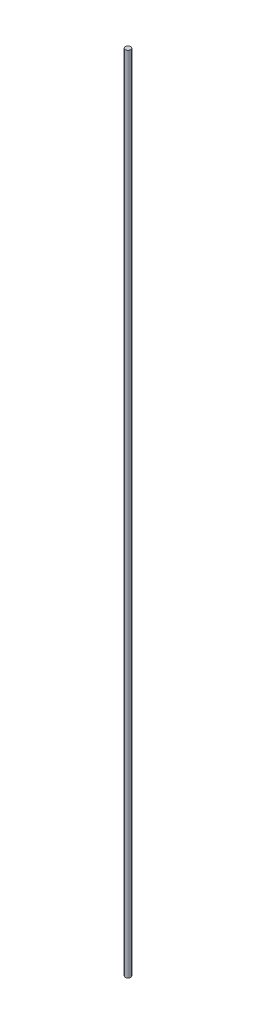
SolidWorks part; units mm, degrees
ref_plane "Front Plane" through (0, 0, 0) normal (0, 0, 1) x (1, 0, 0)
ref_plane "Top Plane" through (0, 0, 0) normal (0, 1, 0) x (1, 0, 0)
ref_plane "Right Plane" through (0, 0, 0) normal (1, 0, 0) x (0, 0, -1)
sketch "Sketch1" plane through (0, 0, 0) normal (0, 1, 0) x (1, 0, 0)
  circle A0 centre (0, 0) radius 3
  dimension "D1" = 6
extrude "Boss-Extrude1" add sketch "Sketch1" along normal blind 900
